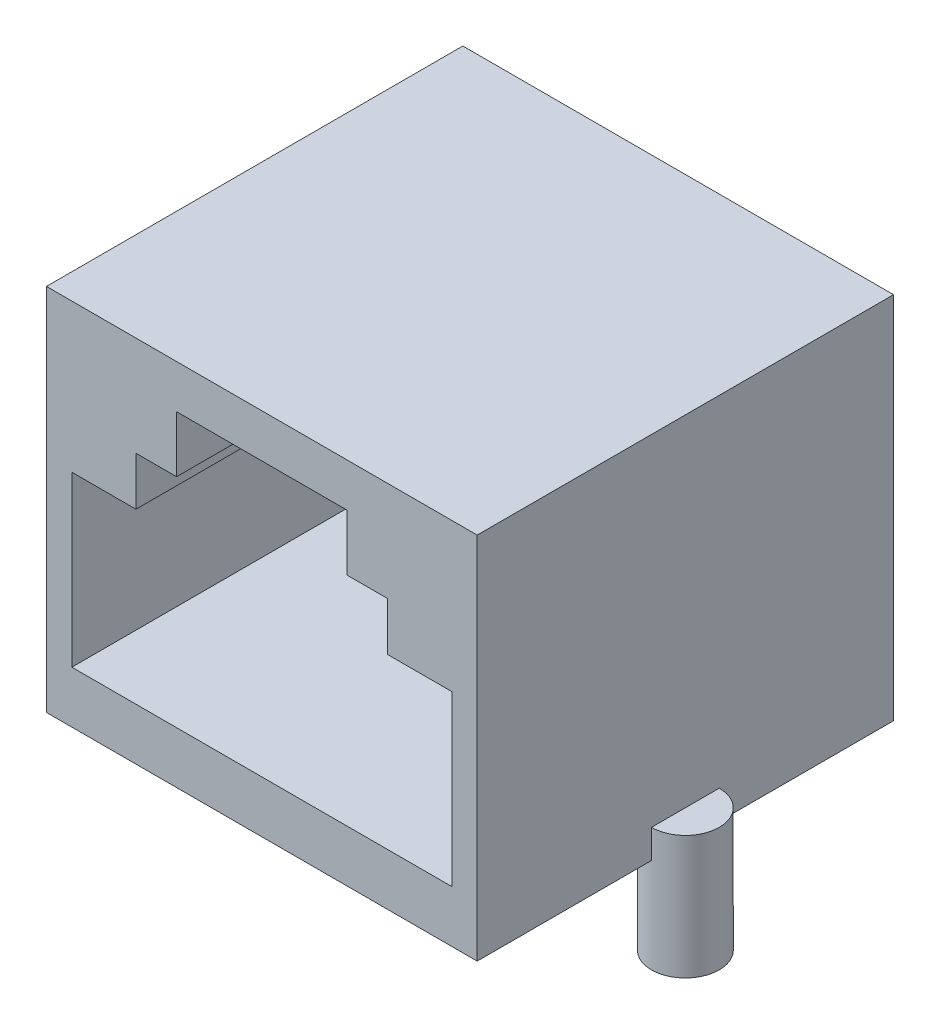
SolidWorks part; units mm, degrees
ref_plane "前视基准面" through (0, 0, 0) normal (0, 0, 1) x (1, 0, 0)
ref_plane "上视基准面" through (0, 0, 0) normal (0, 1, 0) x (1, 0, 0)
ref_plane "右视基准面" through (0, 0, 0) normal (1, 0, 0) x (0, 0, -1)
sketch "草图1" plane through (0, 0, 0) normal (0, 1, 0) x (1, 0, 0)
  line L0 (0, 16.9446) -> (0, -13.3694) construction
  line L1 (-7.5, 7.25) -> (7.5, 7.25)
  line L2 (-7.5, 7.25) -> (-7.5, -7.25)
  line L3 (-7.5, -7.25) -> (7.5, -7.25)
  line L4 (7.5, 7.25) -> (7.5, -7.25)
  line L5 (-15.7193, 0) -> (16.1317, 0) construction
  dimension "D1" = 15
  dimension "D2" = 14.5
extrude "凸台-拉伸1" add sketch "草图1" along normal blind 12.85
sketch "草图2" plane through (0, 0, 0) normal (0, -1, 0) x (1, 0, 0)
  line L0 (-11.6182, 0) -> (15.2039, 0) construction
  line L1 (0, 10.873) -> (0, -11.948) construction
  circle A0 centre (-7.5, 0) radius 1.18
  circle A1 centre (7.5, 0) radius 1.18
  dimension "D1" = 2.36
  dimension "D2" = 15
extrude "凸台-拉伸2" add sketch "草图2" along normal blind 3.3 and the other way blind 1
sketch "草图3" plane through (0, 0, 7.25) normal (0, 0, 1) x (1, 0, 0)
  line L0 (0, -5.598) -> (0, 17.8161) construction
  line L1 (2.9676, 11.3364) -> (-2.9676, 11.3364)
  line L2 (-2.9676, 11.3364) -> (-2.9676, 9.3762)
  line L3 (-2.9676, 9.3762) -> (-4.3833, 9.3762)
  line L4 (-4.3833, 9.3762) -> (-4.3833, 7.6882)
  line L5 (-4.3833, 7.6882) -> (-6.6159, 7.6882)
  line L6 (-6.6159, 7.6882) -> (-6.6159, 1.8074)
  line L7 (-6.6159, 1.8074) -> (6.6159, 1.8074)
  line L8 (6.6159, 7.6882) -> (6.6159, 1.8074)
  line L9 (4.3833, 7.6882) -> (6.6159, 7.6882)
  line L10 (4.3833, 9.3762) -> (4.3833, 7.6882)
  line L11 (2.9676, 9.3762) -> (4.3833, 9.3762)
  line L12 (2.9676, 11.3364) -> (2.9676, 9.3762)
  point P12 (0, 1.8074)
  point P17 (0, 11.3364)
extrude "切除-拉伸1" cut sketch "草图3" against normal blind 10
